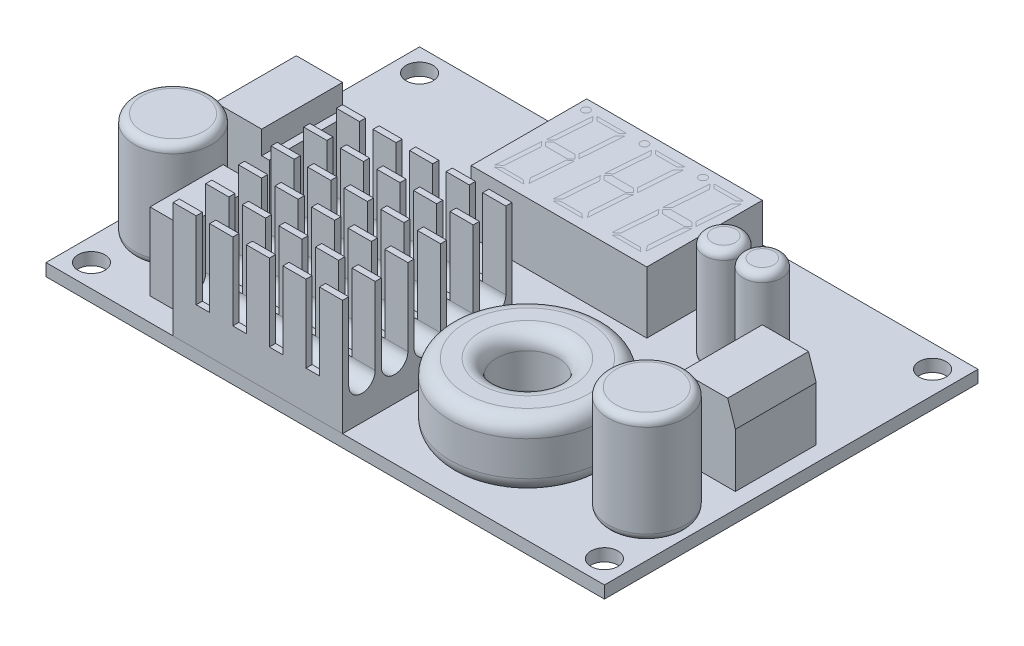
SolidWorks part; units mm, degrees
ref_plane "Alzado" through (0, 0, 0) normal (0, 0, 1) x (1, 0, 0)
ref_plane "Planta" through (0, 0, 0) normal (0, 1, 0) x (1, 0, 0)
ref_plane "Vista lateral" through (0, 0, 0) normal (1, 0, 0) x (0, 0, -1)
sketch "Croquis1" plane through (0, 0, 0) normal (0, 1, 0) x (1, 0, 0)
  line L0 (-36.25, 0) -> (36.25, 0) construction
  line L1 (-36.25, 24.25) -> (36.25, 24.25)
  line L2 (-36.25, 24.25) -> (-36.25, -24.25)
  line L3 (-36.25, -24.25) -> (36.25, -24.25)
  line L4 (36.25, 24.25) -> (36.25, -24.25)
  line L5 (-36.25, 24.25) -> (36.25, -24.25) construction
  line L6 (-36.25, -24.25) -> (36.25, 24.25) construction
  line L7 (0, 24.25) -> (0, -24.25) construction
  circle A0 centre (-33.3, 21.3) radius 1.75
  circle A1 centre (33.3, 21.3) radius 1.75
  circle A2 centre (33.3, -21.3) radius 1.75
  circle A3 centre (-33.3, -21.3) radius 1.75
  point P0 (0, 0)
  point P8 (-35.05, 21.3)
  point P11 (0, 0)
  point P14 (0, 0)
  point P15 (-33.3, 23.05)
  dimension "D3" = 3.5
  dimension "D1" = 72.5
  dimension "D2" = 48.5
  dimension "D4" = 1.2
  dimension "D5" = 1.2
extrude "Saliente-Extruir1" add sketch "Croquis1" along normal blind 1.6
sketch "Croquis3" plane through (0, 1.6, 0) normal (0, 1, 0) x (1, 0, 0)
  line L0 (36.25, 24.25) -> (-36.25, 24.25) construction
  line L1 (-11.55, 21.25) -> (11.25, 21.25)
  line L2 (-11.55, 21.25) -> (-11.55, 6.25)
  line L3 (-11.55, 6.25) -> (11.25, 6.25)
  line L4 (11.25, 21.25) -> (11.25, 6.25)
  line L5 (36.25, -24.25) -> (36.25, 24.25) construction
  dimension "D1" = 22.8
  dimension "D2" = 15
  dimension "D3" = 3
  dimension "D4" = 25
extrude "Saliente-Extruir2" add sketch "Croquis3" along normal blind 8 separate body
sketch "Croquis4" plane through (0, 1.6, 0) normal (0, 1, 0) x (1, 0, 0)
  line L0 (36.25, -24.25) -> (36.25, 24.25) construction
  line L1 (-36.25, -24.25) -> (36.25, -24.25) construction
  line L2 (36.25, 24.25) -> (-36.25, 24.25) construction
  circle A0 centre (30.75, -13.25) radius 5
  circle A1 centre (18.75, 8.75) radius 2.5
  circle A2 centre (23.75, 8.75) radius 2.5
  point P3 (35.75, -13.25)
  point P5 (30.75, -18.25)
  point P13 (23.75, 11.25)
  point P15 (26.25, 8.75)
  dimension "D1" = 10
  dimension "D6" = 5
  dimension "D2" = 0.5
  dimension "D3" = 6
  dimension "D4" = 13
  dimension "D5" = 10
extrude "Saliente-Extruir3" add sketch "Croquis4" along normal blind 14 separate body contours A0 | A1 | A2
fillet "Redondeo3" radius 1 2 edges at (30.75, 1.6, 18.25) (30.75, 15.6, 18.25)
fillet "Redondeo4" radius 1 2 edges at (23.75, 15.6, -6.25) (23.75, 1.6, -6.25)
fillet "Redondeo5" radius 1 2 edges at (18.75, 15.6, -6.25) (18.75, 1.6, -6.25)
mirror "Simetría1" about plane through (0, 0, 0) normal (1, 0, 0) of bodies 105 103
sketch "Croquis5" plane through (0, 1.6, 0) normal (0, 1, 0) x (1, 0, 0)
  line L0 (36.25, -24.25) -> (36.25, 24.25) construction
  line L1 (26.25, 5.25) -> (34.25, 5.25)
  line L2 (26.25, 5.25) -> (26.25, -5.25)
  line L3 (26.25, -5.25) -> (34.25, -5.25)
  line L4 (34.25, 5.25) -> (34.25, -5.25)
  line L5 (36.25, 24.25) -> (-36.25, 24.25) construction
  dimension "D1" = 10.5
  dimension "D2" = 8
  dimension "D3" = 2
  dimension "D4" = 19
extrude "Saliente-Extruir4" add sketch "Croquis5" along normal blind 10 separate body
sketch "Croquis6" plane through (0, 0, -5.25) normal (0, 0, -1) x (-1, 0, 0)
  line L0 (-34.25, 8.6) -> (-33.25, 11.6)
  line L1 (-34.25, 11.6) -> (-34.25, 1.6) construction
  line L2 (-34.25, 11.6) -> (-26.25, 11.6) construction
  line L3 (-34.25, 1.6) -> (-26.25, 1.6) construction
  line L4 (-27.25, 11.6) -> (-27.25, 8.6)
  line L5 (-27.25, 8.6) -> (-26.25, 8.6)
  line L6 (-26.25, 11.6) -> (-26.25, 1.6) construction
  line L7 (-34.25, 8.6) -> (-34.25, 11.6)
  line L8 (-34.25, 11.6) -> (-33.25, 11.6)
  line L9 (-27.25, 11.6) -> (-26.25, 11.6)
  line L10 (-26.25, 11.6) -> (-26.25, 8.6)
  dimension "D1" = 7
  dimension "D2" = 1
  dimension "D3" = 1
extrude "Cortar-Extruir1" cut sketch "Croquis6" against normal up to next (10.5 mm away)
mirror "Simetría2" about plane through (0, 0, 0) normal (1, 0, 0) of bodies 109
sketch "Croquis7" plane through (0, 1.6, 0) normal (0, 1, 0) x (1, 0, 0)
  line L0 (-36.25, -24.25) -> (36.25, -24.25) construction
  line L1 (-25.75, -11.75) -> (-21.25, -11.75)
  line L2 (-25.75, -11.75) -> (-25.75, -21.25)
  line L3 (-25.75, -21.25) -> (-21.25, -21.25)
  line L4 (-21.25, -11.75) -> (-21.25, -21.25)
  circle A0 centre (-30.75, -13.25) radius 5 construction
  dimension "D1" = 4.5
  dimension "D2" = 9.5
  dimension "D3" = 3
extrude "Saliente-Extruir5" add sketch "Croquis7" along normal blind 10 separate body
sketch "Croquis8" plane through (0, 1.6, 0) normal (0, 1, 0) x (1, 0, 0)
  line L0 (-21.25, -21.25) -> (-21.25, -11.75) construction
  line L1 (-19.75, -2.25) -> (2.25, -2.25)
  line L2 (-19.75, -2.25) -> (-19.75, -24.25)
  line L3 (-19.75, -24.25) -> (2.25, -24.25)
  line L4 (2.25, -2.25) -> (2.25, -24.25)
  line L5 (-36.25, -24.25) -> (36.25, -24.25) construction
  dimension "D1" = 22
  dimension "D2" = 1.5
extrude "Saliente-Extruir6" add sketch "Croquis8" along normal blind 15 separate body
sketch "Croquis9" plane through (0, 16.6, 0) normal (0, 1, 0) x (1, 0, 0)
  line L0 (-15, -2.25) -> (-15, -3.05)
  line L3 (-19.75, -3.05) -> (-16.75, -3.05)
  line L4 (-16.75, -2.25) -> (-16.75, -3.05)
  line L6 (-12, -2.25) -> (-12, -3.05)
  line L7 (-15, -3.05) -> (-12, -3.05)
  line L8 (-10.25, -2.25) -> (-10.25, -3.05)
  line L10 (-7.25, -2.25) -> (-7.25, -3.05)
  line L11 (-10.25, -3.05) -> (-7.25, -3.05)
  line L12 (-5.5, -2.25) -> (-5.5, -3.05)
  line L14 (-2.5, -2.25) -> (-2.5, -3.05)
  line L15 (-5.5, -3.05) -> (-2.5, -3.05)
  line L16 (-0.75, -2.25) -> (-0.75, -3.05)
  line L19 (-0.75, -3.05) -> (2.25, -3.05)
  line L20 (-15, -6.49) -> (-15, -7.29)
  line L21 (-15, -6.49) -> (-12, -6.49)
  line L22 (-12, -6.49) -> (-12, -7.29)
  line L23 (-15, -7.29) -> (-12, -7.29)
  line L24 (-10.25, -6.49) -> (-10.25, -7.29)
  line L25 (-10.25, -6.49) -> (-7.25, -6.49)
  line L26 (-7.25, -6.49) -> (-7.25, -7.29)
  line L27 (-10.25, -7.29) -> (-7.25, -7.29)
  line L28 (-5.5, -6.49) -> (-5.5, -7.29)
  line L29 (-5.5, -6.49) -> (-2.5, -6.49)
  line L30 (-2.5, -6.49) -> (-2.5, -7.29)
  line L31 (-5.5, -7.29) -> (-2.5, -7.29)
  line L32 (-0.75, -6.49) -> (-0.75, -7.29)
  line L33 (-0.75, -6.49) -> (2.25, -6.49)
  line L35 (-0.75, -7.29) -> (2.25, -7.29)
  line L36 (-15, -10.73) -> (-15, -11.53)
  line L37 (-15, -10.73) -> (-12, -10.73)
  line L38 (-12, -10.73) -> (-12, -11.53)
  line L39 (-15, -11.53) -> (-12, -11.53)
  line L40 (-10.25, -10.73) -> (-10.25, -11.53)
  line L41 (-10.25, -10.73) -> (-7.25, -10.73)
  line L42 (-7.25, -10.73) -> (-7.25, -11.53)
  line L43 (-10.25, -11.53) -> (-7.25, -11.53)
  line L44 (-5.5, -10.73) -> (-5.5, -11.53)
  line L45 (-5.5, -10.73) -> (-2.5, -10.73)
  line L46 (-2.5, -10.73) -> (-2.5, -11.53)
  line L47 (-5.5, -11.53) -> (-2.5, -11.53)
  line L48 (-0.75, -10.73) -> (-0.75, -11.53)
  line L49 (-0.75, -10.73) -> (2.25, -10.73)
  line L51 (-0.75, -11.53) -> (2.25, -11.53)
  line L52 (-15, -14.97) -> (-15, -15.77)
  line L53 (-15, -14.97) -> (-12, -14.97)
  line L54 (-12, -14.97) -> (-12, -15.77)
  line L55 (-15, -15.77) -> (-12, -15.77)
  line L56 (-10.25, -14.97) -> (-10.25, -15.77)
  line L57 (-10.25, -14.97) -> (-7.25, -14.97)
  line L58 (-7.25, -14.97) -> (-7.25, -15.77)
  line L59 (-10.25, -15.77) -> (-7.25, -15.77)
  line L60 (-5.5, -14.97) -> (-5.5, -15.77)
  line L61 (-5.5, -14.97) -> (-2.5, -14.97)
  line L62 (-2.5, -14.97) -> (-2.5, -15.77)
  line L63 (-5.5, -15.77) -> (-2.5, -15.77)
  line L64 (-0.75, -14.97) -> (-0.75, -15.77)
  line L65 (-0.75, -14.97) -> (2.25, -14.97)
  line L67 (-0.75, -15.77) -> (2.25, -15.77)
  line L68 (-15, -19.21) -> (-15, -20.01)
  line L69 (-15, -19.21) -> (-12, -19.21)
  line L70 (-12, -19.21) -> (-12, -20.01)
  line L71 (-15, -20.01) -> (-12, -20.01)
  line L72 (-10.25, -19.21) -> (-10.25, -20.01)
  line L73 (-10.25, -19.21) -> (-7.25, -19.21)
  line L74 (-7.25, -19.21) -> (-7.25, -20.01)
  line L75 (-10.25, -20.01) -> (-7.25, -20.01)
  line L76 (-5.5, -19.21) -> (-5.5, -20.01)
  line L77 (-5.5, -19.21) -> (-2.5, -19.21)
  line L78 (-2.5, -19.21) -> (-2.5, -20.01)
  line L79 (-5.5, -20.01) -> (-2.5, -20.01)
  line L80 (-0.75, -19.21) -> (-0.75, -20.01)
  line L81 (-0.75, -19.21) -> (2.25, -19.21)
  line L83 (-0.75, -20.01) -> (2.25, -20.01)
  line L84 (-15, -23.45) -> (-15, -24.25)
  line L85 (-15, -23.45) -> (-12, -23.45)
  line L86 (-12, -23.45) -> (-12, -24.25)
  line L88 (-10.25, -23.45) -> (-10.25, -24.25)
  line L89 (-10.25, -23.45) -> (-7.25, -23.45)
  line L90 (-7.25, -23.45) -> (-7.25, -24.25)
  line L92 (-5.5, -23.45) -> (-5.5, -24.25)
  line L93 (-5.5, -23.45) -> (-2.5, -23.45)
  line L94 (-2.5, -23.45) -> (-2.5, -24.25)
  line L96 (-0.75, -23.45) -> (-0.75, -24.25)
  line L97 (-0.75, -23.45) -> (2.25, -23.45)
  line L101 (-19.75, -6.49) -> (-16.75, -6.49)
  line L102 (-16.75, -6.49) -> (-16.75, -7.29)
  line L103 (-19.75, -7.29) -> (-16.75, -7.29)
  line L105 (-19.75, -10.73) -> (-16.75, -10.73)
  line L106 (-16.75, -10.73) -> (-16.75, -11.53)
  line L107 (-19.75, -11.53) -> (-16.75, -11.53)
  line L109 (-19.75, -14.97) -> (-16.75, -14.97)
  line L110 (-16.75, -14.97) -> (-16.75, -15.77)
  line L111 (-19.75, -15.77) -> (-16.75, -15.77)
  line L113 (-19.75, -19.21) -> (-16.75, -19.21)
  line L114 (-16.75, -19.21) -> (-16.75, -20.01)
  line L115 (-19.75, -20.01) -> (-16.75, -20.01)
  line L117 (-19.75, -23.45) -> (-16.75, -23.45)
  line L118 (-16.75, -23.45) -> (-16.75, -24.25)
  line L120 (-19.75, -20.01) -> (-19.75, -23.45)
  line L121 (-16.75, -24.25) -> (-15, -24.25)
  line L122 (-12, -24.25) -> (-10.25, -24.25)
  line L123 (-7.25, -24.25) -> (-5.5, -24.25)
  line L124 (-2.5, -24.25) -> (-0.75, -24.25)
  line L125 (2.25, -23.45) -> (2.25, -20.01)
  line L126 (2.25, -19.21) -> (2.25, -15.77)
  line L127 (2.25, -14.97) -> (2.25, -11.53)
  line L128 (2.25, -7.29) -> (2.25, -10.73)
  line L129 (2.25, -6.49) -> (2.25, -3.05)
  line L130 (-0.75, -2.25) -> (-2.5, -2.25)
  line L131 (-5.5, -2.25) -> (-7.25, -2.25)
  line L132 (-10.25, -2.25) -> (-12, -2.25)
  line L133 (-15, -2.25) -> (-16.75, -2.25)
  line L134 (-19.75, -3.05) -> (-19.75, -6.49)
  line L135 (-19.75, -7.29) -> (-19.75, -10.73)
  line L136 (-19.75, -11.53) -> (-19.75, -14.97)
  line L137 (-19.75, -15.77) -> (-19.75, -19.21)
  line L139 (2.25, -24.25) -> (2.25, -2.25) construction
  line L141 (-19.75, -24.25) -> (-16.75, -24.25) [skipped]
  line L142 (-15, -24.25) -> (-12, -24.25) [skipped]
  line L143 (-10.25, -24.25) -> (-7.25, -24.25) [skipped]
  line L144 (-5.5, -24.25) -> (-2.5, -24.25) [skipped]
  line L145 (-0.75, -24.25) -> (2.25, -24.25) [skipped]
  line L146 (2.25, -23.45) -> (2.25, -24.25) [skipped]
  line L147 (2.25, -19.21) -> (2.25, -20.01) [skipped]
  line L148 (2.25, -14.97) -> (2.25, -15.77) [skipped]
  line L149 (2.25, -10.73) -> (2.25, -11.53) [skipped]
  line L150 (2.25, -6.49) -> (2.25, -7.29) [skipped]
  line L152 (2.25, -2.25) -> (2.25, -3.05) [skipped]
  line L156 (2.25, -2.25) -> (-19.75, -2.25) construction
  dimension "D1" = 3
  dimension "D2" = 3.44
  dimension "D5" = 1.75
  dimension "D6" = 0.8
  dimension "D7" = 3.44
  dimension "D3" = 5
  dimension "D4" = 6
extrude "Cortar-Extruir2" cut sketch "Croquis9" against normal blind 10
sketch "Croquis10" plane through (2.25, 0, 0) normal (1, 0, 0) x (0, 0, -1)
  line L0 (-23.45, 6.6) -> (-20.01, 6.6) construction
  line L1 (-23.45, 6.6) -> (-20.01, 6.6)
  line L2 (-19.21, 6.6) -> (-15.77, 6.6)
  line L3 (-14.97, 6.6) -> (-11.53, 6.6)
  line L4 (-10.73, 6.6) -> (-7.29, 6.6)
  line L5 (-6.49, 6.6) -> (-3.05, 6.6)
  line L6 (-19.21, 6.6) -> (-19.21, 16.6) construction
  arc A0 (-23.45, 6.6) -> (-20.01, 6.6) centre (-21.73, 6.6) ccw
  arc A1 (-19.21, 6.6) -> (-15.77, 6.6) centre (-17.49, 6.6) ccw
  arc A2 (-14.97, 6.6) -> (-11.53, 6.6) centre (-13.25, 6.6) ccw
  arc A3 (-10.73, 6.6) -> (-7.29, 6.6) centre (-9.01, 6.6) ccw
  arc A4 (-6.49, 6.6) -> (-3.05, 6.6) centre (-4.77, 6.6) ccw
  dimension "D1" = 5
extrude "Cortar-Extruir3" cut sketch "Croquis10" against normal up to body
ref_plane "Plano1" through (14.25, 0, 0) normal (1, 0, 0) x (0, 0, -1)
sketch "Croquis11" plane through (14.25, 0, 0) normal (1, 0, 0) x (0, 0, -1)
  line L0 (-12.25, 1.6) -> (-12.25, 21.4589) construction
  line L1 (-24.25, 1.6) -> (24.25, 1.6) construction
  line L2 (-24.25, 1.6) -> (-24.25, 0) construction
  line L4 (-22.25, 1.6) -> (-16.25, 1.6)
  line L5 (-22.25, 1.6) -> (-22.25, 10.1)
  line L6 (-22.25, 10.1) -> (-16.25, 10.1)
  line L7 (-16.25, 1.6) -> (-16.25, 10.1)
  dimension "D1" = 12
  dimension "D2" = 10
  dimension "D3" = 6
  dimension "D4" = 8.5
revolve "Revolución1" add sketch "Croquis11" angle 360 about L0
fillet "Redondeo6" radius 2 4 edges at (14.25, 1.6, 8.25) (14.25, 10.1, 8.25) (14.25, 1.6, 2.25) (14.25, 10.1, 2.25)
sketch "Croquis12" plane through (0, 9.6, 0) normal (0, 1, 0) x (1, 0, 0)
  line L0 (-3.95, 21.25) -> (-3.95, 6.25) construction
  line L1 (11.25, 21.25) -> (-11.55, 21.25) construction
  line L2 (-11.55, 6.25) -> (11.25, 6.25) construction
  line L3 (-11.55, 21.25) -> (-11.55, 6.25) construction
  line L4 (3.65, 21.25) -> (3.65, 6.25) construction
  line L5 (11.25, 6.25) -> (11.25, 21.25) construction
  line L6 (-11.55, 13.75) -> (11.25, 13.75) construction
  line L7 (-9.1507, 19.95) -> (-10.1055, 7.5885) construction
  line L8 (-10.1055, 7.5885) -> (-5.804, 7.5885) construction
  line L9 (-5.804, 7.5885) -> (-4.8493, 19.95) construction
  line L10 (-9.1507, 19.95) -> (-4.8493, 19.95) construction
  line L11 (-9.3789, 13.75) -> (-8.8789, 14.25)
  line L12 (-8.8789, 14.25) -> (-6.0789, 14.25)
  line L13 (-6.0789, 14.25) -> (-5.5789, 13.75)
  line L14 (-5.5789, 13.75) -> (-6.0789, 13.25)
  line L15 (-6.0789, 13.25) -> (-8.8789, 13.25)
  line L16 (-8.8789, 13.25) -> (-9.3789, 13.75)
  line L17 (-7.4789, 14.25) -> (-7.4789, 13.25) construction
  line L18 (-8.9, 19.95) -> (-8.4, 19.45)
  line L19 (-8.4, 19.45) -> (-5.6, 19.45)
  line L20 (-5.6, 19.45) -> (-5.1, 19.95)
  line L21 (-7, 19.45) -> (-7, 19.95) construction
  line L22 (-8.9, 19.95) -> (-5.1, 19.95)
  line L23 (-9.17, 19.7007) -> (-8.618, 19.0563)
  line L24 (-8.618, 19.0563) -> (-8.9644, 14.5705)
  line L25 (-8.9644, 14.5705) -> (-9.6089, 14.0185)
  line L26 (-9.6089, 14.0185) -> (-9.17, 19.7007)
  line L27 (-9.8555, 7.5885) -> (-9.3167, 8.05)
  line L28 (-9.3167, 8.05) -> (-6.5928, 8.05)
  line L29 (-6.5928, 8.05) -> (-6.054, 7.5885)
  line L30 (-7.9548, 7.5885) -> (-7.9548, 8.05) construction
  line L31 (-9.8555, 7.5885) -> (-6.054, 7.5885)
  line L32 (-9.6281, 13.7693) -> (-5.3521, 13.439) construction
  line L33 (-8.7912, 16.8134) -> (-9.3894, 16.8596) construction
  line L34 (-9.1507, 19.95) -> (-9.17, 19.7007) construction
  line L35 (-9.0954, 12.8756) -> (-9.6474, 13.52)
  line L36 (-9.4418, 8.3898) -> (-9.0954, 12.8756)
  line L37 (-10.0862, 7.8378) -> (-9.4418, 8.3898)
  line L38 (-9.6474, 13.52) -> (-10.0862, 7.8378)
  line L39 (-4.8815, 19.5321) -> (-5.3089, 13.9993)
  line L40 (-5.3089, 13.9993) -> (-5.8675, 14.5579)
  line L41 (-5.8675, 14.5579) -> (-5.5337, 18.8799)
  line L42 (-5.5337, 18.8799) -> (-4.8815, 19.5321)
  line L43 (-5.3281, 13.75) -> (-9.6041, 14.0803) construction
  line L44 (-1.3, 19.95) -> (2.5, 19.95)
  line L45 (-5.9852, 13.0345) -> (-6.319, 8.7125)
  line L46 (-5.3474, 13.5007) -> (-5.9852, 13.0345)
  line L47 (-5.7747, 7.9679) -> (-5.3474, 13.5007)
  line L48 (-6.319, 8.7125) -> (-5.7747, 7.9679)
  line L49 (2, 19.45) -> (2.5, 19.95)
  line L50 (-0.8, 19.45) -> (2, 19.45)
  line L51 (-1.3, 19.95) -> (-0.8, 19.45)
  line L52 (-2.0089, 14.0185) -> (-1.57, 19.7007)
  line L53 (-1.57, 19.7007) -> (-1.018, 19.0563)
  line L54 (-1.018, 19.0563) -> (-1.3644, 14.5705)
  line L55 (-1.3644, 14.5705) -> (-2.0089, 14.0185)
  line L56 (2.0663, 18.8799) -> (2.7185, 19.5321)
  line L57 (2.7185, 19.5321) -> (2.2911, 13.9993)
  line L58 (2.2911, 13.9993) -> (1.7325, 14.5579)
  line L59 (1.7325, 14.5579) -> (2.0663, 18.8799)
  line L60 (-1.2789, 13.25) -> (-1.7789, 13.75)
  line L61 (-1.7789, 13.75) -> (-1.2789, 14.25)
  line L62 (-1.2789, 14.25) -> (1.5211, 14.25)
  line L63 (1.5211, 14.25) -> (2.0211, 13.75)
  line L64 (2.0211, 13.75) -> (1.5211, 13.25)
  line L65 (1.5211, 13.25) -> (-1.2789, 13.25)
  line L66 (-1.4954, 12.8756) -> (-2.0474, 13.52)
  line L67 (-2.0474, 13.52) -> (-2.4862, 7.8378)
  line L68 (-2.4862, 7.8378) -> (-1.8418, 8.3898)
  line L69 (-1.8418, 8.3898) -> (-1.4954, 12.8756)
  line L70 (-2.2555, 7.5885) -> (1.546, 7.5885)
  line L71 (1.0072, 8.05) -> (1.546, 7.5885)
  line L72 (-1.7167, 8.05) -> (1.0072, 8.05)
  line L73 (-2.2555, 7.5885) -> (-1.7167, 8.05)
  line L74 (1.6148, 13.0345) -> (1.281, 8.7125)
  line L75 (1.281, 8.7125) -> (1.8253, 7.9679)
  line L76 (1.8253, 7.9679) -> (2.2526, 13.5007)
  line L77 (2.2526, 13.5007) -> (1.6148, 13.0345)
  line L78 (6.3, 19.95) -> (10.1, 19.95)
  line L79 (9.6, 19.45) -> (10.1, 19.95)
  line L80 (6.8, 19.45) -> (9.6, 19.45)
  line L81 (6.3, 19.95) -> (6.8, 19.45)
  line L82 (5.5911, 14.0185) -> (6.03, 19.7007)
  line L83 (6.03, 19.7007) -> (6.582, 19.0563)
  line L84 (6.582, 19.0563) -> (6.2356, 14.5705)
  line L85 (6.2356, 14.5705) -> (5.5911, 14.0185)
  line L86 (9.6663, 18.8799) -> (10.3185, 19.5321)
  line L87 (10.3185, 19.5321) -> (9.8911, 13.9993)
  line L88 (9.8911, 13.9993) -> (9.3325, 14.5579)
  line L89 (9.3325, 14.5579) -> (9.6663, 18.8799)
  line L90 (6.3211, 13.25) -> (5.8211, 13.75)
  line L91 (5.8211, 13.75) -> (6.3211, 14.25)
  line L92 (6.3211, 14.25) -> (9.1211, 14.25)
  line L93 (9.1211, 14.25) -> (9.6211, 13.75)
  line L94 (9.6211, 13.75) -> (9.1211, 13.25)
  line L95 (9.1211, 13.25) -> (6.3211, 13.25)
  line L96 (6.1046, 12.8756) -> (5.5526, 13.52)
  line L97 (5.5526, 13.52) -> (5.1138, 7.8378)
  line L98 (5.1138, 7.8378) -> (5.7582, 8.3898)
  line L99 (5.7582, 8.3898) -> (6.1046, 12.8756)
  line L100 (5.3445, 7.5885) -> (9.146, 7.5885)
  line L101 (8.6072, 8.05) -> (9.146, 7.5885)
  line L102 (5.8833, 8.05) -> (8.6072, 8.05)
  line L103 (5.3445, 7.5885) -> (5.8833, 8.05)
  line L104 (9.2148, 13.0345) -> (8.881, 8.7125)
  line L105 (8.881, 8.7125) -> (9.4253, 7.9679)
  line L106 (9.4253, 7.9679) -> (9.8526, 13.5007)
  line L107 (9.8526, 13.5007) -> (9.2148, 13.0345)
  circle A0 centre (-10.35, 19.95) radius 0.5
  circle A1 centre (-2.75, 19.95) radius 0.5
  circle A2 centre (4.85, 19.95) radius 0.5
  point P50 (-5.3281, 13.75)
  dimension "D18" = 1
  dimension "D1" = 7.6
  dimension "D2" = 7.6
  dimension "D3" = 0.25
  dimension "D4" = 0.25
  dimension "D5" = 45
  dimension "D6" = 0.25
  dimension "D7" = 0.25
  dimension "D8" = 0.5
  dimension "D9" = 45
  dimension "D10" = 0.5
  dimension "D11" = 0.25
  dimension "D12" = 0.25
  dimension "D13" = 0.6
  dimension "D14" = 0.25
  dimension "D15" = 0.25
  dimension "D16" = 0.6
  dimension "D17" = 0.25
  dimension "D19" = 1.2
  dimension "D20" = 1.3
  dimension "D21" = 1.45
  dimension "D22" = 1.4
  dimension "D23" = 0.45
  dimension "D24" = 0.45
  dimension "D25" = 3
  dimension "D26" = 1.2
split line "Línea de partición1"
